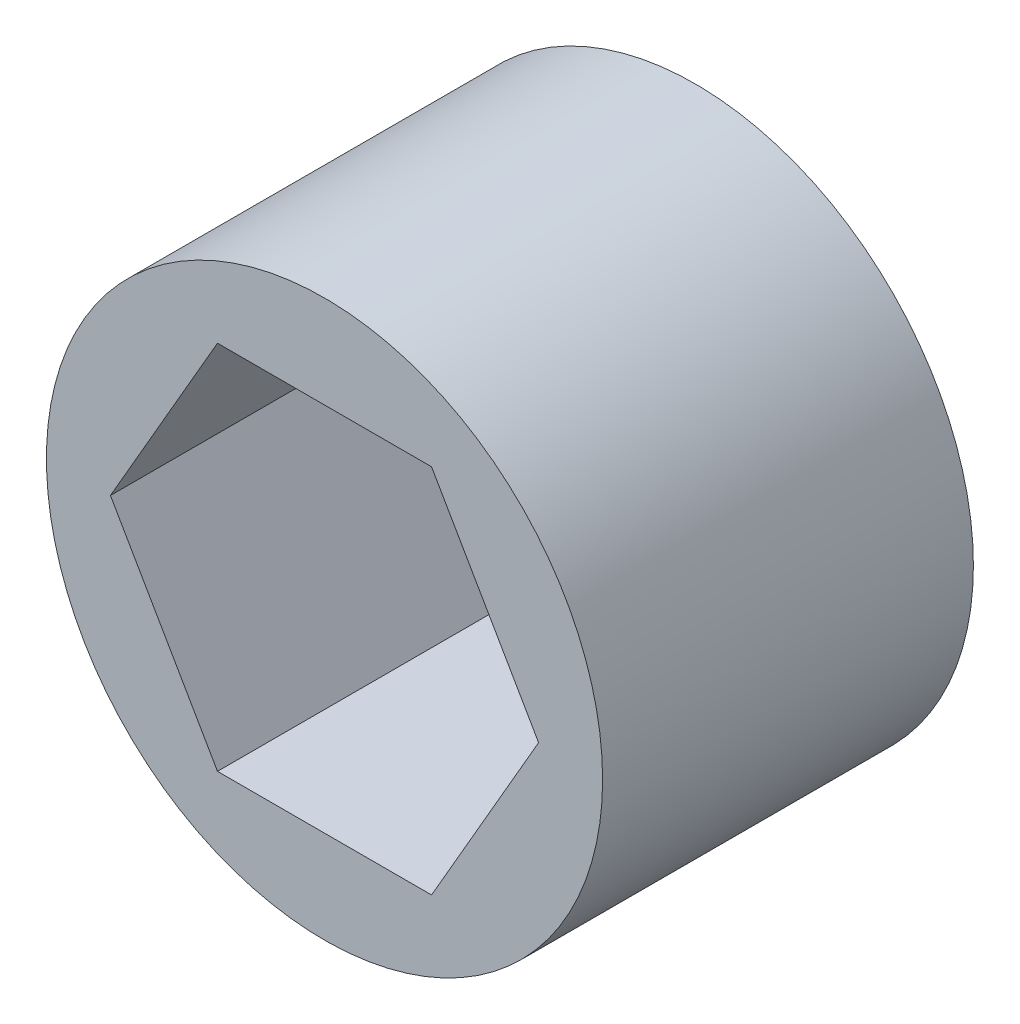
SolidWorks part; units mm, degrees
material "Nylon 101"
ref_plane "Front Plane" through (0, 0, 0) normal (0, 0, 1) x (1, 0, 0)
ref_plane "Top Plane" through (0, 0, 0) normal (0, 1, 0) x (1, 0, 0)
ref_plane "Right Plane" through (0, 0, 0) normal (1, 0, 0) x (0, 0, -1)
sketch "Sketch1" plane through (0, 0, 0) normal (0, 0, 1) x (1, 0, 0)
  line L1 (-3.6662, 6.35) -> (-7.3323, 0)
  line L2 (-7.3323, 0) -> (-3.6662, -6.35)
  line L3 (-3.6662, -6.35) -> (3.6662, -6.35)
  line L4 (3.6662, -6.35) -> (7.3323, 0)
  line L5 (7.3323, 0) -> (3.6662, 6.35)
  line L6 (3.6662, 6.35) -> (-3.6662, 6.35)
  circle A0 centre (0, 0) radius 6.35 construction
  circle A1 centre (0, 0) radius 9.525
  point P10 (0, 6.35)
  dimension "D1" = 12.7
  dimension "D2" = 19.05
extrude "Boss-Extrude1" add sketch "Sketch1" along normal blind 12.7
